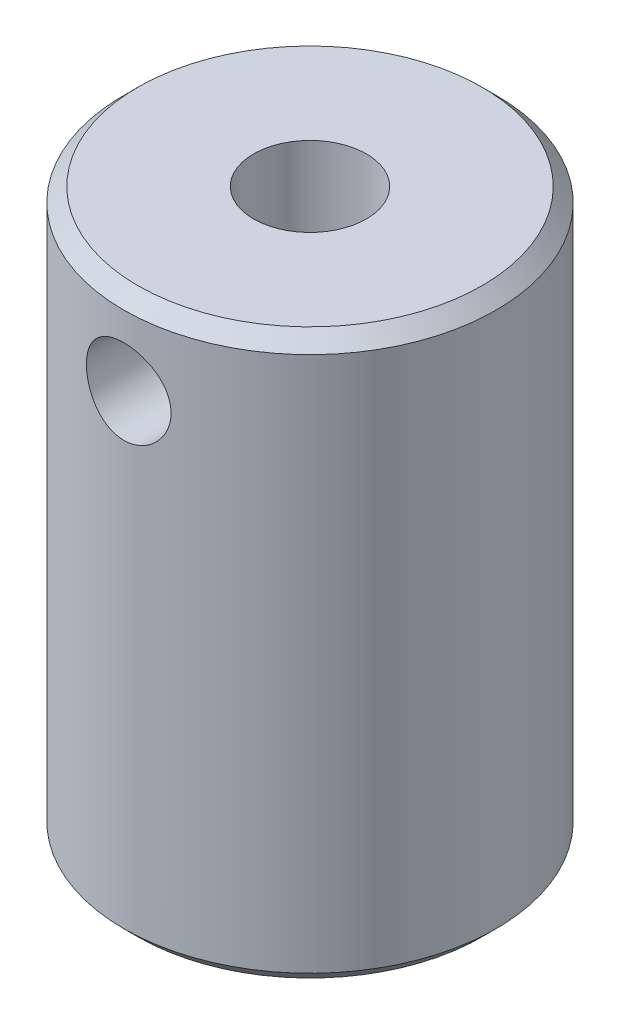
SolidWorks part; units mm, degrees
material "6061-T4 (SS)"
ref_plane "前视基准面" through (0, 0, 0) normal (0, 0, 1) x (1, 0, 0)
ref_plane "上视基准面" through (0, 0, 0) normal (0, 1, 0) x (1, 0, 0)
ref_plane "右视基准面" through (0, 0, 0) normal (1, 0, 0) x (0, 0, -1)
sketch "草图1" plane through (0, 0, 0) normal (0, 1, 0) x (1, 0, 0)
  circle A0 centre (0, 0) radius 6.6
  dimension "D1" = 13.2
extrude "凸台-拉伸1" add sketch "草图1" along normal blind 18.8 and the other way blind 1.2
chamfer "倒角1" distance 0.5 angle 45 2 edges at (0, -1.2, 6.6) (0, 18.8, 6.6)
sketch "草图2" plane through (0, 18.8, 0) normal (0, 1, 0) x (1, 0, 0)
  circle A0 centre (0, 0) radius 2
  dimension "D1" = 4
extrude "切除-拉伸1" cut sketch "草图2" against normal blind 13.4
sketch "草图3" plane through (0, 0, 0) normal (0, 0, 1) x (1, 0, 0)
  line L0 (6.1, 18.8) -> (-6.1, 18.8) construction
  circle A0 centre (0, 15.8) radius 1.5
  dimension "D1" = 3
  dimension "D2" = 3
extrude "切除-拉伸2" cut sketch "草图3" along normal blind 13.4
